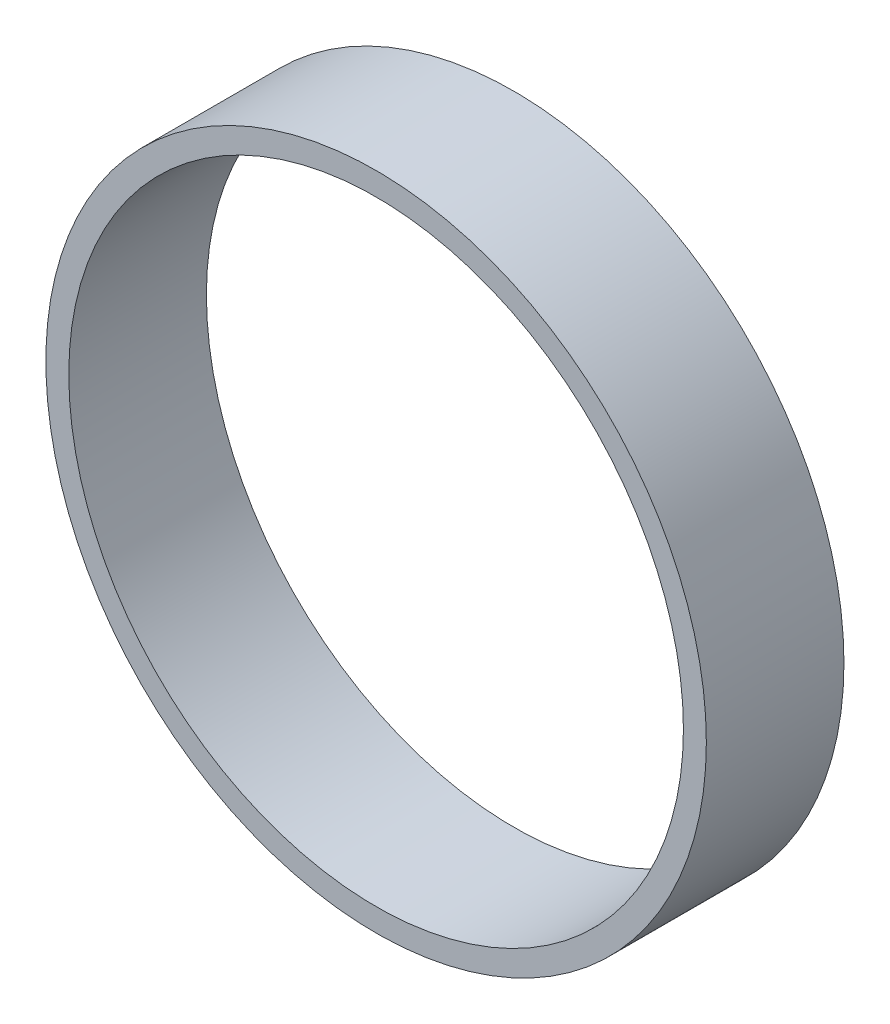
SolidWorks part; units mm, degrees
material "Balsa"
ref_plane "Ebene vorne" through (0, 0, 0) normal (0, 0, 1) x (1, 0, 0)
ref_plane "Ebene oben" through (0, 0, 0) normal (0, 1, 0) x (1, 0, 0)
ref_plane "Ebene rechts" through (0, 0, 0) normal (1, 0, 0) x (0, 0, -1)
sketch "Sketch1" plane through (0, 0, 0) normal (0, 0, 1) x (1, 0, 0)
  circle A0 centre (0, 0) radius 72
  circle A1 centre (0, 0) radius 67
  dimension "D1" = 144
  dimension "D2" = 5
extrude "Boss-Extrude1" add sketch "Sketch1" along normal blind 30
